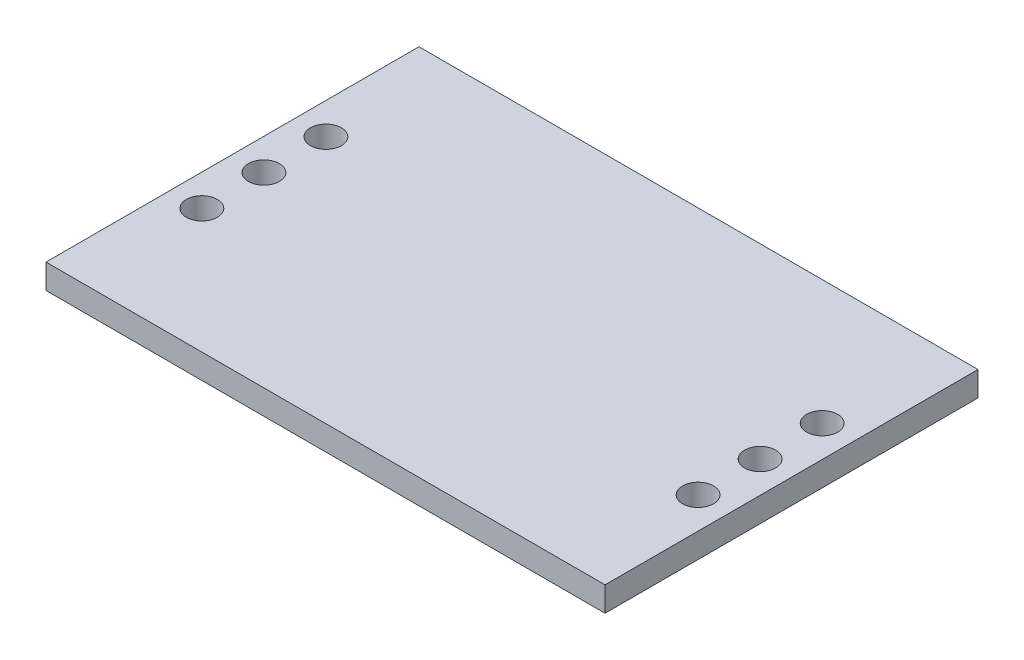
SolidWorks part; units mm, degrees
ref_plane "Front Plane" through (0, 0, 0) normal (0, 0, 1) x (1, 0, 0)
ref_plane "Top Plane" through (0, 0, 0) normal (0, 1, 0) x (1, 0, 0)
ref_plane "Right Plane" through (0, 0, 0) normal (1, 0, 0) x (0, 0, -1)
sketch "Sketch2" plane through (0, 0, 0) normal (0, 1, 0) x (1, 0, 0)
  line L0 (-49.4853, 19.9506) -> (22.6147, 19.9506)
  line L1 (22.6147, 19.9506) -> (22.6147, -28.1494)
  line L2 (22.6147, -28.1494) -> (-49.4853, -28.1494)
  line L3 (-49.4853, -28.1494) -> (-49.4853, 19.9506)
extrude "Boss-Extrude1" add sketch "Sketch2" along normal blind 3.175
sketch "Sketch3" plane through (0, 3.175, 0) normal (0, 1, 0) x (1, 0, 0)
  line L0 (-13.4353, 19.9506) -> (-13.4353, -28.1494)
  line L1 (22.6147, 19.9506) -> (-49.4853, 19.9506) construction
  line L2 (-49.4853, -28.1494) -> (22.6147, -28.1494) construction
  line L3 (-13.4353, -4.0994) -> (18.5647, -4.0994)
  circle A0 centre (18.5647, -4.0994) radius 2
  circle A1 centre (18.5647, -0.0994) radius 1.5
  circle A3 centre (18.5647, 3.9006) radius 2
  circle A4 centre (18.5647, -8.0994) radius 1.5
  circle A5 centre (18.5647, -12.0994) radius 2
  circle A6 centre (-45.4353, -12.0994) radius 2
  circle A7 centre (-45.4353, -8.0994) radius 1.5
  circle A8 centre (-45.4353, -4.0994) radius 2
  circle A9 centre (-45.4353, -0.0994) radius 1.5
  circle A10 centre (-45.4353, 3.9006) radius 2
  dimension "D1" = 4
  dimension "D2" = 8
  dimension "D3" = 16
extrude "Cut-Extrude1" cut sketch "Sketch3" against normal blind 3.175 contours A8 | A5 | A0 | A3 | A6 | A10
